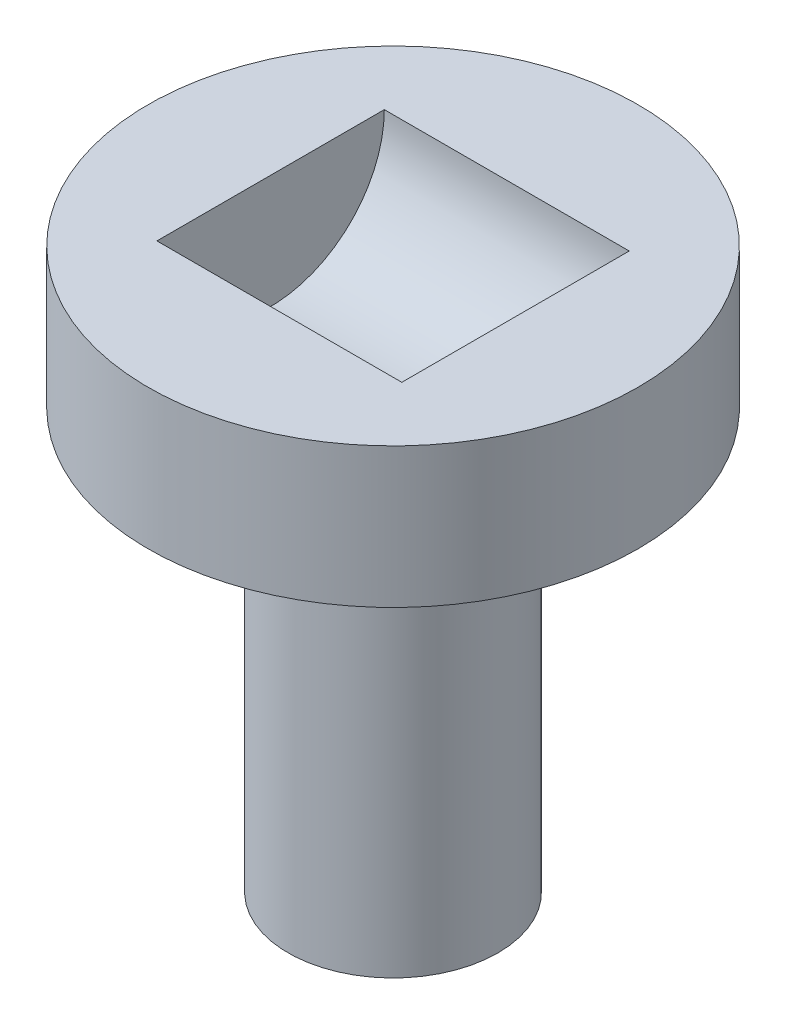
SolidWorks part; units mm, degrees
ref_plane "前视基准面" through (0, 0, 0) normal (0, 0, 1) x (1, 0, 0)
ref_plane "上视基准面" through (0, 0, 0) normal (0, 1, 0) x (1, 0, 0)
ref_plane "右视基准面" through (0, 0, 0) normal (1, 0, 0) x (0, 0, -1)
sketch "草图1" plane through (0, 0, 0) normal (0, 0, 1) x (1, 0, 0)
  line L0 (0, -147.5589) -> (0, 7230.3844) construction
  line L2 (0, 8) -> (7, 8)
  line L3 (7, 8) -> (7, 4)
  line L4 (7, 4) -> (5, 4)
  line L5 (3, 2) -> (3, -8)
  line L6 (3, -8) -> (1.22, -8)
  line L7 (1.22, -8) -> (1.22, 0)
  line L8 (1.22, 0) -> (0, 0)
  line L10 (0, 8) -> (0, 0)
  arc A0 (5, 4) -> (3, 2) centre (5, 2) ccw
revolve "旋转1" add sketch "草图1" angle 360 about L0
sketch "草图2" plane through (0, 0, 0) normal (1, 0, 0) x (0, 0, -1)
  line L0 (0, -1000) -> (0, 49000) construction
  line L1 (7, 8) -> (-7, 8) construction
  circle A0 centre (0, 8) radius 3.25
  dimension "D1" = 6.5
extrude "切除-拉伸1" cut sketch "草图2" against normal mid plane 7
